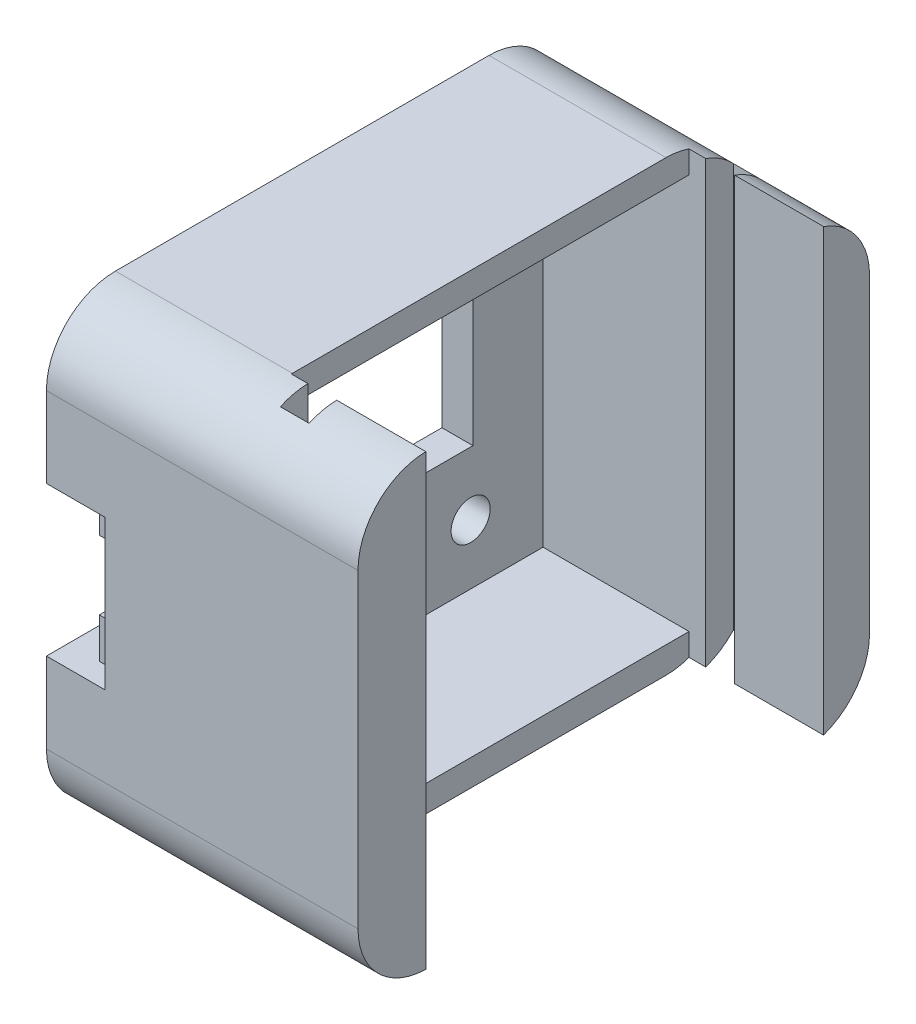
SolidWorks part; units mm, degrees
ref_plane "Front Plane" through (0, 0, 0) normal (0, 0, 1) x (1, 0, 0)
ref_plane "Top Plane" through (0, 0, 0) normal (0, 1, 0) x (1, 0, 0)
ref_plane "Right Plane" through (0, 0, 0) normal (1, 0, 0) x (0, 0, -1)
ref_plane "Plane1" through (193.9, 0, 0) normal (1, 0, 0) x (0, 0, -1)
ref_plane "Plane2" through (196.6, 0, 0) normal (1, 0, 0) x (0, 0, -1)
sketch "Sketch1" plane through (193.9, 0, 0) normal (1, 0, 0) x (0, 0, -1)
  line L1 (-322.3, -19.5) -> (-279.7, -19.5)
  line L2 (-322.3, -19.5) -> (-322.3, 19.5)
  line L3 (-322.3, 19.5) -> (-279.7, 19.5)
  line L4 (-279.7, -19.5) -> (-279.7, 19.5)
extrude "Boss-Extrude1" add sketch "Sketch1" along normal blind 2.7
sketch "Sketch2" plane through (196.6, 0, 0) normal (1, 0, 0) x (0, 0, -1)
  line L1 (-322.3, 17.2) -> (-279.7, 17.2)
  line L2 (-322.3, 17.2) -> (-322.3, 19.5)
  line L3 (-322.3, 19.5) -> (-279.7, 19.5)
  line L4 (-279.7, 17.2) -> (-279.7, 19.5)
  line L6 (-322.3, -19.5) -> (-279.7, -19.5)
  line L7 (-322.3, -19.5) -> (-322.3, -17.2)
  line L8 (-322.3, -17.2) -> (-279.7, -17.2)
  line L9 (-279.7, -19.5) -> (-279.7, -17.2)
extrude "Boss-Extrude2" add sketch "Sketch2" along normal blind 12.7
sketch "Sketch3" plane through (196.6, 0, 0) normal (1, 0, 0) x (0, 0, -1)
  line L1 (-322.3, -19.5) -> (-318.3, -19.5)
  line L2 (-322.3, -19.5) -> (-322.3, 19.5)
  line L3 (-322.3, 19.5) -> (-318.3, 19.5)
  line L4 (-318.3, -19.5) -> (-318.3, 19.5)
  line L6 (-283.7, -19.5) -> (-279.7, -19.5)
  line L7 (-283.7, -19.5) -> (-283.7, 19.5)
  line L8 (-283.7, 19.5) -> (-279.7, 19.5)
  line L9 (-279.7, -19.5) -> (-279.7, 19.5)
extrude "Boss-Extrude3" add sketch "Sketch3" along normal blind 18.4
sketch "Sketch4" plane through (193.9, 0, 0) normal (1, 0, 0) x (0, 0, -1)
  line L1 (-323, -6.5) -> (-289.8, -6.5)
  line L2 (-323, -6.5) -> (-323, 6.5)
  line L3 (-323, 6.5) -> (-289.8, 6.5)
  line L4 (-289.8, -6.5) -> (-289.8, 6.5)
  circle A0 centre (-290, 12) radius 1.7
  circle A1 centre (-290, -12) radius 1.7
  circle A2 centre (-312, 12) radius 1.7
  circle A3 centre (-312, -12) radius 1.7
extrude "Cut-Extrude1" cut sketch "Sketch4" along normal blind 2.7
sketch "Sketch5" plane through (196.6, 0, 0) normal (1, 0, 0) x (0, 0, -1)
  line L1 (-323, -3) -> (-318.3, -3)
  line L2 (-323, -3) -> (-323, 3)
  line L3 (-323, 3) -> (-318.3, 3)
  line L4 (-318.3, -3) -> (-318.3, 3)
extrude "Cut-Extrude2" cut sketch "Sketch5" along normal blind 2.4
sketch "Sketch6" plane through (0, 0, 0) normal (0, 1, 0) x (1, 0, 0)
  line L1 (210.75, -320.7) -> (213.25, -320.7)
  line L2 (210.75, -320.7) -> (210.75, -318.3)
  line L3 (210.75, -318.3) -> (213.25, -318.3)
  line L4 (213.25, -320.7) -> (213.25, -318.3)
  line L6 (210.75, -283.7) -> (213.25, -283.7)
  line L7 (210.75, -283.7) -> (210.75, -281.3)
  line L8 (210.75, -281.3) -> (213.25, -281.3)
  line L9 (213.25, -283.7) -> (213.25, -281.3)
extrude "Cut-Extrude3" cut sketch "Sketch6" along normal mid plane 60
ref_plane "Plane3" through (215, 0, 0) normal (1, 0, 0) x (0, 0, -1)
sketch "Sketch7" plane through (215, 0, 0) normal (1, 0, 0) x (0, 0, -1)
  line L1 (-324.2, -19.5) -> (-318.3, -19.5)
  line L2 (-324.2, -19.5) -> (-324.2, 19.5)
  line L3 (-324.2, 19.5) -> (-318.3, 19.5)
  line L4 (-318.3, -19.5) -> (-318.3, 19.5)
  line L6 (-283.7, -19.5) -> (-279.7, -19.5)
  line L7 (-283.7, -19.5) -> (-283.7, 19.5)
  line L8 (-283.7, 19.5) -> (-279.7, 19.5)
  line L9 (-279.7, -19.5) -> (-279.7, 19.5)
extrude "Boss-Extrude4" add sketch "Sketch7" along normal blind 6
ref_plane "Plane4" through (0, 0, 322.3) normal (0, 0, 1) x (1, 0, 0)
sketch "Sketch8" plane through (0, 0, 322.3) normal (0, 0, 1) x (1, 0, 0)
  line L0 (193.9, -19.5) -> (215, -19.5)
  line L1 (215, -19.5) -> (215, 19.5)
  line L2 (215, 19.5) -> (193.9, 19.5)
  line L3 (193.9, 19.5) -> (193.9, 6.5)
  line L4 (193.9, 6.5) -> (199, 6.5)
  line L5 (199, 6.5) -> (199, -6.5)
  line L6 (199, -6.5) -> (193.9, -6.5)
  line L7 (193.9, -6.5) -> (193.9, -19.5)
extrude "Boss-Extrude5" add sketch "Sketch8" along normal blind 1.9
sketch "Sketch9" plane through (193.9, 0, 0) normal (1, 0, 0) x (0, 0, -1)
  line L0 (-324.2, 13.5) -> (-325.5, 13.5)
  line L1 (-325.5, 13.5) -> (-325.5, 20.5)
  line L2 (-325.5, 20.5) -> (-318.2, 20.5)
  line L3 (-318.2, 20.5) -> (-318.2, 19.5)
  line L4 (-324.2, -13.5) -> (-325.5, -13.5)
  line L5 (-325.5, -13.5) -> (-325.5, -20.5)
  line L6 (-325.5, -20.5) -> (-318.2, -20.5)
  line L7 (-318.2, -20.5) -> (-318.2, -19.5)
  line L8 (-279.7, 13.5) -> (-278.4, 13.5)
  line L9 (-278.4, 13.5) -> (-278.4, 20.5)
  line L10 (-278.4, 20.5) -> (-285.7, 20.5)
  line L11 (-285.7, 20.5) -> (-285.7, 19.5)
  line L12 (-279.7, -13.5) -> (-278.4, -13.5)
  line L13 (-278.4, -13.5) -> (-278.4, -20.5)
  line L14 (-278.4, -20.5) -> (-285.7, -20.5)
  line L15 (-285.7, -20.5) -> (-285.7, -19.5)
  arc A0 (-318.2, 19.5) -> (-324.2, 13.5) centre (-318.2, 13.5) ccw
  arc A1 (-318.2, -19.5) -> (-324.2, -13.5) centre (-318.2, -13.5) cw
  arc A2 (-285.7, 19.5) -> (-279.7, 13.5) centre (-285.7, 13.5) cw
  arc A3 (-285.7, -19.5) -> (-279.7, -13.5) centre (-285.7, -13.5) ccw
extrude "Cut-Extrude4" cut sketch "Sketch9" along normal through all
